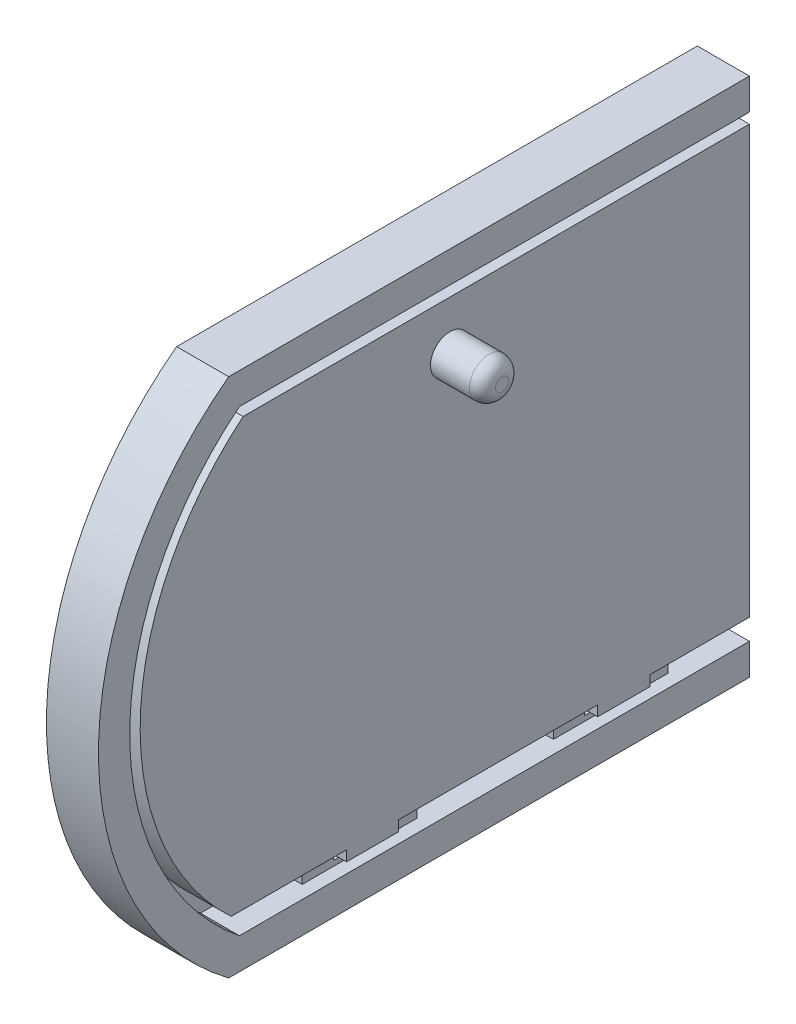
SolidWorks part; units mm, degrees
ref_plane "Alzado" through (0, 0, 0) normal (1, 0, 0) x (0, 1, 0)
ref_plane "Planta" through (0, 0, 0) normal (0, 0, 1) x (0, 1, 0)
ref_plane "Vista lateral" through (0, 0, 0) normal (0, 1, 0) x (-1, 0, 0)
sketch "Croquis1" plane through (0, 0, 0) normal (1, 0, 0) x (0, 1, 0)
  line L0 (0, -125) -> (0, 125) construction
  line L1 (100, -125) -> (-100, -125) construction
  line L2 (-100, -125) -> (-100, 75)
  line L3 (100, -125) -> (100, 75)
  line L4 (80, -105) -> (80, 68.0074)
  line L6 (-80, -105) -> (-80, 68.0074)
  line L7 (80, -105) -> (-80, -105) construction
  line L8 (-80, -105) -> (-80, -125)
  line L9 (80, -105) -> (80, -125)
  line L10 (-100, -125) -> (-80, -125)
  line L11 (80, -125) -> (100, -125)
  arc A0 (-100, 75) -> (100, 75) centre (0, 0) cw
  arc A1 (-80, 68.0074) -> (80, 68.0074) centre (0, 0) cw
  point P4 (0, 0)
  point P12 (0, 125)
  dimension "D1" = 50
  dimension "D2" = 200
  dimension "D3" = 200
  dimension "D4" = 20
extrude "Saliente-Extruir1" add sketch "Croquis1" along normal blind 20
sketch "Croquis2" plane through (20, 0, 0) normal (1, 0, 0) x (0, 1, 0)
  line L3 (80, 68.0074) -> (80, -125) construction
  line L4 (-80, -125) -> (-80, 68.0074) construction
  line L5 (88, 70.8872) -> (88, -125)
  line L6 (-88, -125) -> (-88, 70.8872)
  line L7 (88, 70.8872) -> (88, -125)
  line L8 (-88, -125) -> (-88, 70.8872)
  line L9 (80, 68.0074) -> (80, -125)
  line L10 (-80, -125) -> (-80, 68.0074)
  line L11 (-88, -125) -> (-80, -125)
  line L12 (80, -125) -> (88, -125)
  arc A3 (80, 68.0074) -> (-80, 68.0074) centre (0, 0) ccw construction
  arc A4 (88, 70.8872) -> (-88, 70.8872) centre (0, 0) ccw
  arc A5 (88, 70.8872) -> (-88, 70.8872) centre (0, 0) ccw
  arc A6 (80, 68.0074) -> (-80, 68.0074) centre (0, 0) ccw
  dimension "D1" = 8
extrude "Cortar-Extruir1" cut sketch "Croquis2" against normal blind 5
sketch "Croquis3" plane through (15, 0, 0) normal (1, 0, 0) x (0, 1, 0)
  line L0 (-80, -28.4963) -> (80, -28.4963) construction
  line L1 (-80, -125) -> (-80, 68.0074) construction
  line L2 (80, 68.0074) -> (80, -125) construction
  line L3 (-80, -28.4963) -> (-80, -125) construction
  line L4 (-88, -125) -> (-80, -125) construction
  line L5 (-86, -66.7482) -> (-80, -66.7482)
  line L6 (-86, -66.7482) -> (-86, -86.7482)
  line L7 (-86, -86.7482) -> (-80, -86.7482)
  line L8 (-80, -66.7482) -> (-80, -86.7482)
  line L9 (-86, 29.7555) -> (-80, 29.7555)
  line L10 (-80, 9.7555) -> (-80, 29.7555)
  line L11 (-86, 9.7555) -> (-80, 9.7555)
  line L12 (-86, 9.7555) -> (-86, 29.7555)
  point P12 (-80, -76.7482)
  point P13 (-80, -76.7482)
  dimension "D1" = 20
  dimension "D2" = 6
extrude "Cortar-Extruir2" cut sketch "Croquis3" against normal blind 10
sketch "Croquis4" plane through (0, 0, 29.7555) normal (0, 0, -1) x (1, 0, 0)
  line L0 (5, 86) -> (15, 86) construction
  line L1 (5, 86) -> (5, 80) construction
  circle A0 centre (10, 83) radius 2.75
  point P4 (10, 86)
  point P7 (5, 83)
  dimension "D1" = 5.5
extrude "Cortar-Extruir3" cut sketch "Croquis4" against normal blind 10
ref_plane "Plano1" through (0, 0, 19.7555) normal (0, 0, -1) x (-1, 0, 0)
mirror "Simetría1" about plane through (0, 0, 19.7555) normal (0, 0, -1) of "Cortar-Extruir3"
ref_plane "Plano2" through (0, 0, -28.4963) normal (0, 0, -1) x (-1, 0, 0)
mirror "Simetría2" about plane through (0, 0, -28.4963) normal (0, 0, -1) of "Simetría1", "Cortar-Extruir3"
sketch "Croquis5" plane through (15, 0, 0) normal (1, 0, 0) x (0, 1, 0)
  line L0 (-80, -125) -> (84, -125)
  line L1 (-84, 29.7555) -> (-80, 29.7555)
  line L2 (-80, 29.7555) -> (-86, 29.7555) construction
  line L3 (-80, 29.7555) -> (-80, 74.0338)
  line L4 (-84, 9.7555) -> (-80, 9.7555)
  line L5 (-86, 9.7555) -> (-80, 9.7555) construction
  line L6 (-80, -66.7482) -> (-80, 9.7555)
  line L7 (-80, -66.7482) -> (-84, -66.7482)
  line L8 (-80, -66.7482) -> (-86, -66.7482) construction
  line L9 (-84, -86.7482) -> (-80, -86.7482)
  line L10 (-86, -86.7482) -> (-80, -86.7482) construction
  line L11 (-80, -86.7482) -> (-80, -125)
  line L12 (-84, -66.7482) -> (-84, -86.7482)
  line L18 (84, -125) -> (84, 69.4622)
  line L19 (-84, 69.4622) -> (-84, -125)
  line L20 (84, -125) -> (84, 69.4622)
  line L21 (-84, 29.7555) -> (-84, 9.7555)
  arc A4 (84, 69.4622) -> (-84, 69.4622) centre (0, 0) ccw
  arc A5 (84, 69.4622) -> (-80, 74.0338) centre (0, 0) ccw
  dimension "D1" = 4
extrude "Saliente-Extruir2" add sketch "Croquis5" along normal blind 5 and the other way blind 10 separate body
sketch "Croquis6" plane through (0, 0, 29.7555) normal (0, 0, 1) x (1, 0, 0)
  circle A2 centre (10, -83) radius 2.25
  circle A3 centre (10, -83) radius 2.25
  dimension "D1" = 0.5
extrude "Saliente-Extruir3" add sketch "Croquis6" along normal blind 9
mirror "Simetría3" about plane through (0, 0, 19.7555) normal (0, 0, -1) of "Saliente-Extruir3"
mirror "Simetría4" about plane through (0, 0, -28.4963) normal (0, 0, -1) of "Simetría3", "Saliente-Extruir3"
sketch "Croquis7" plane through (15, 0, 0) normal (1, 0, 0) x (0, 1, 0)
  line L0 (-88, -98.7482) -> (-80, -98.7482)
  line L1 (-80.25, -96.7482) -> (-85.75, -96.7482) construction
  line L2 (-88, -54.7482) -> (-80, -54.7482)
  line L3 (-85.75, -56.7482) -> (-80.25, -56.7482) construction
  line L4 (-88, 41.7555) -> (-80, 41.7555)
  line L5 (-88, -2.2445) -> (-80, -2.2445)
  line L6 (-85.75, 39.7555) -> (-80.25, 39.7555) construction
  line L7 (-80.25, -0.2445) -> (-85.75, -0.2445) construction
  line L8 (-88, -2.2445) -> (-88, -54.7482)
  line L9 (-88, -98.7482) -> (-88, -125)
  line L14 (-86, -66.7482) -> (-80, -66.7482)
  line L15 (-80, -66.7482) -> (-80, 9.7555)
  line L16 (-80, 9.7555) -> (-86, 9.7555)
  line L17 (-86, 9.7555) -> (-86, 29.7555)
  line L18 (-86, 29.7555) -> (-80, 29.7555)
  line L19 (-80, 29.7555) -> (-80, 68.0074)
  line L20 (80, 68.0074) -> (80, -125)
  line L21 (80, -125) -> (88, -125)
  line L22 (88, -125) -> (88, 70.8872)
  line L23 (-88, 70.8872) -> (-88, -125)
  line L24 (-88, -125) -> (-80, -125)
  line L25 (-80, -125) -> (-80, -86.7482)
  line L26 (-80, -86.7482) -> (-86, -86.7482)
  line L27 (-86, -86.7482) -> (-86, -66.7482)
  line L29 (-80, -54.7482) -> (-80, -2.2445)
  line L33 (-80, 41.7555) -> (-80, 68.0074)
  line L34 (80, 68.0074) -> (80, -125)
  line L35 (80, -125) -> (88, -125)
  line L36 (88, -125) -> (88, 70.8872)
  line L37 (-88, 70.8872) -> (-88, 41.7555)
  line L38 (-88, -125) -> (-80, -125)
  line L39 (-80, -125) -> (-80, -98.7482)
  arc A2 (80, 68.0074) -> (-80, 68.0074) centre (0, 0) ccw
  arc A3 (88, 70.8872) -> (-88, 70.8872) centre (0, 0) ccw
  arc A4 (80, 68.0074) -> (-80, 68.0074) centre (0, 0) ccw
  arc A5 (88, 70.8872) -> (-88, 70.8872) centre (0, 0) ccw
  dimension "D2" = 2
  dimension "D3" = 2
  dimension "D4" = 2
  dimension "D5" = 2
  dimension "D1" = 0
extrude "Cortar-Extruir4" cut sketch "Croquis7" against normal blind 10
sketch "Croquis8" plane through (20, 0, 0) normal (1, 0, 0) x (0, 1, 0)
  circle A0 centre (65, -10) radius 7.5
  dimension "D2" = 15
  dimension "D1" = 65
  dimension "D3" = 10
extrude "Saliente-Extruir5" add sketch "Croquis8" along normal blind 20
fillet "Redondeo1" radius 5 1 edges at (40, 65, -17.5)
